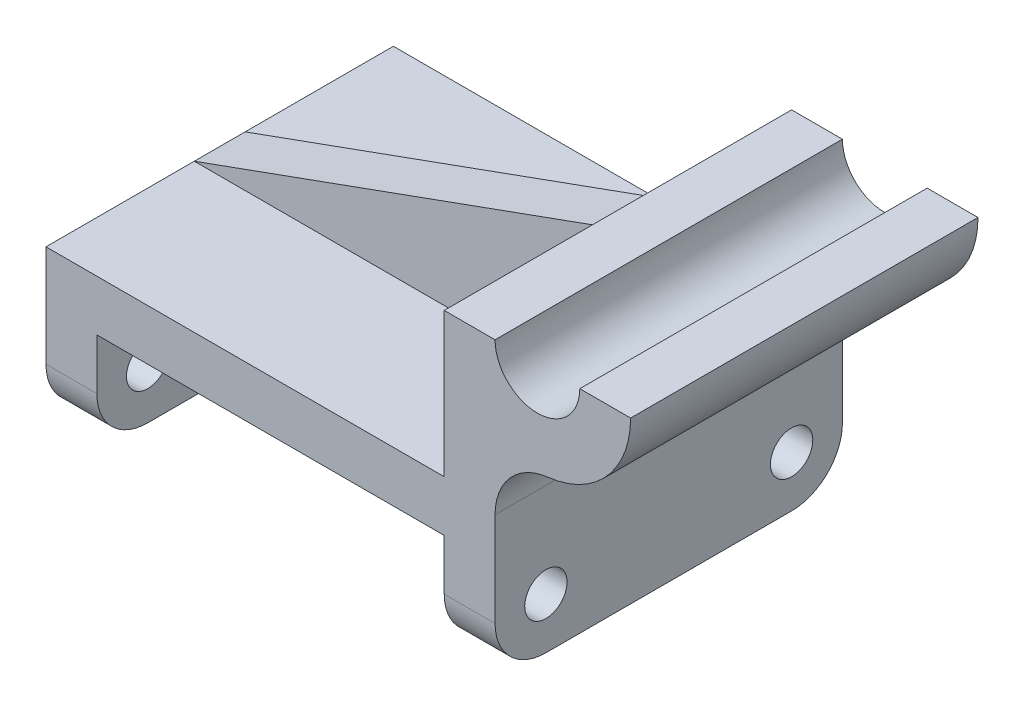
SolidWorks part; units mm, degrees
ref_plane "Front Plane" through (0, 0, 0) normal (0, 0, 1) x (1, 0, 0)
ref_plane "Top Plane" through (0, 0, 0) normal (0, 1, 0) x (1, 0, 0)
ref_plane "Right Plane" through (0, 0, 0) normal (1, 0, 0) x (0, 0, -1)
sketch "Sketch1" plane through (0, 0, 0) normal (0, 0, 1) x (1, 0, 0)
  line L11 (-1346.2, -609.6) -> (-1346.2, 304.8)
  line L12 (-1346.2, 304.8) -> (1041.4, 304.8)
  line L13 (1041.4, 304.8) -> (1041.4, 1168.4)
  line L14 (1041.4, 1168.4) -> (1346.2, 1168.4)
  line L15 (1346.2, 1168.4) -> (1346.2, -609.6)
  line L16 (1346.2, -609.6) -> (1041.4, -609.6)
  line L17 (1041.4, -609.6) -> (1041.4, 0)
  line L18 (1041.4, 0) -> (-1041.4, 0)
  line L19 (-1041.4, 0) -> (-1041.4, -609.6)
  line L20 (-1041.4, -609.6) -> (-1346.2, -609.6)
  point P2 (0, 0)
  dimension "D1" = 914.4
  dimension "D2" = 863.6
  dimension "D3" = 180
  dimension "D4" = 304.8
  dimension "D5" = 304.8
  dimension "D6" = 2692.4
extrude "Boss-Extrude4" add sketch "Sketch1" along normal blind 2082.8
sketch "Sketch3" plane through (0, 304.8, 0) normal (0, 1, 0) x (1, 0, 0)
  line L0 (-1346.2, -1041.4) -> (1041.4, -1041.4)
  line L1 (-1346.2, -2082.8) -> (-1346.2, 0) construction
  line L2 (1041.4, -2082.8) -> (1041.4, 0) construction
  line L4 (-1346.2, -889) -> (1041.4, -889)
  line L5 (-1346.2, -889) -> (-1346.2, -1193.8)
  line L6 (-1346.2, -1193.8) -> (1041.4, -1193.8)
  line L7 (1041.4, -889) -> (1041.4, -1193.8)
  line L8 (-1346.2, -889) -> (1041.4, -1193.8) construction
  line L9 (-1346.2, -1193.8) -> (1041.4, -889) construction
  point P6 (-152.4, -1041.4)
  dimension "D1" = 304.8
extrude "Boss-Extrude5" add sketch "Sketch3" along normal blind 863.6 contours L5 L4 L7 L6
sketch "Sketch4" plane through (0, 0, 1193.8) normal (0, 0, 1) x (1, 0, 0)
  line L0 (-1346.2, 304.8) -> (1041.4, 1168.4)
  line L1 (1041.4, 1168.4) -> (-1346.2, 1168.4)
  line L2 (-1346.2, 1168.4) -> (-1346.2, 304.8)
extrude "Cut-Extrude1" cut sketch "Sketch4" against normal blind 863.6
sketch "Sketch6" plane through (0, 0, 1193.8) normal (0, 0, 1) x (1, 0, 0)
  line L0 (1041.4, 1168.4) -> (1346.2, 1168.4)
  line L1 (1854.2, 1168.4) -> (2159, 1168.4)
  arc A0 (1346.2, 1168.4) -> (1854.2, 1168.4) centre (1600.2, 1168.4) ccw
  arc A1 (1041.4, 1168.4) -> (2159, 1168.4) centre (1600.2, 1168.4) ccw
  dimension "D2" = 508
  dimension "D3" = 1117.6
  dimension "D1" = 1117.6
extrude "Boss-Extrude7" add sketch "Sketch6" against normal through all and the other way through all
fillet "Fillet3" radius 355.6 1 edges at (1346.2, 670.6637, 1041.4)
fillet "Fillet4" radius 304.8 1 edges at (-1193.8, -609.6, 0)
fillet "Fillet5" radius 304.8 1 edges at (-1193.8, -609.6, 2082.8)
fillet "Fillet6" radius 304.8 1 edges at (1193.8, -609.6, 2082.8)
fillet "Fillet7" radius 304.8 1 edges at (1193.8, -609.6, 0)
sketch "Sketch9" plane through (-1346.2, 0, 0) normal (-1, 0, 0) x (0, 0, 1)
  circle A1 centre (1778, -304.8) radius 127
  circle A2 centre (304.8, -304.8) radius 127
  dimension "D1" = 254
  dimension "D2" = 254
extrude "Cut-Extrude2" cut sketch "Sketch9" against normal through all contours A2 | A1
